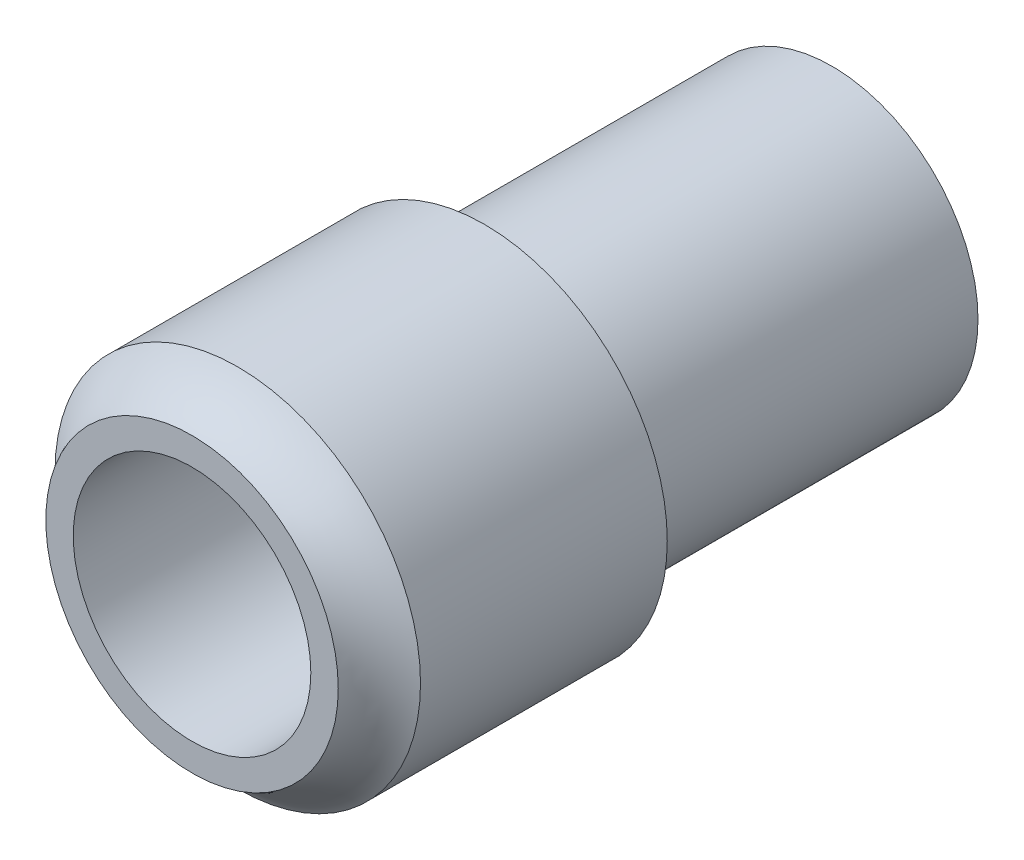
SolidWorks part; units mm, degrees
other "Детальный элемент1"
other "Детальный элемент2"
other "Детальный элемент3"
ref_plane "Спереди" through (0, 0, 0) normal (0, 0, 1) x (1, 0, 0)
ref_plane "Сверху" through (0, 0, 0) normal (0, 1, 0) x (1, 0, 0)
ref_plane "Справа" through (0, 0, 0) normal (1, 0, 0) x (0, 0, -1)
sketch "Эскиз1" plane through (0, 0, 0) normal (1, 0, 0) x (0, 0, -1)
  line L0 (0, 8) -> (0, 10)
  line L1 (0, 10) -> (-13.5, 10)
  line L3 (-16, 8) -> (-16, 0)
  line L4 (-16, 0) -> (19, 0)
  line L5 (19, 0) -> (19, 8)
  line L6 (19, 8) -> (0, 8)
  arc A0 (-13.5, 10) -> (-16, 8) centre (-17.7091, 12.6988) cw
  dimension "D7" = 5
  dimension "D1" = 35
  dimension "D2" = 16
  dimension "D3" = 8
  dimension "D4" = 10
  dimension "D5" = 8
  dimension "D6" = 2.5
revolve "Повернуть1" add sketch "Эскиз1" angle 360 about L4
cosmetic thread "Условное изображение резьбы1" parameters "D1"=16, "D2"=13.797
sketch "Эскиз2" plane through (0, 0, 16) normal (0, 0, 1) x (1, 0, 0)
  circle A0 centre (0, 0) radius 6.5
  dimension "D1" = 13
extrude "Вырез-Вытянуть1" cut sketch "Эскиз2" against normal through all
